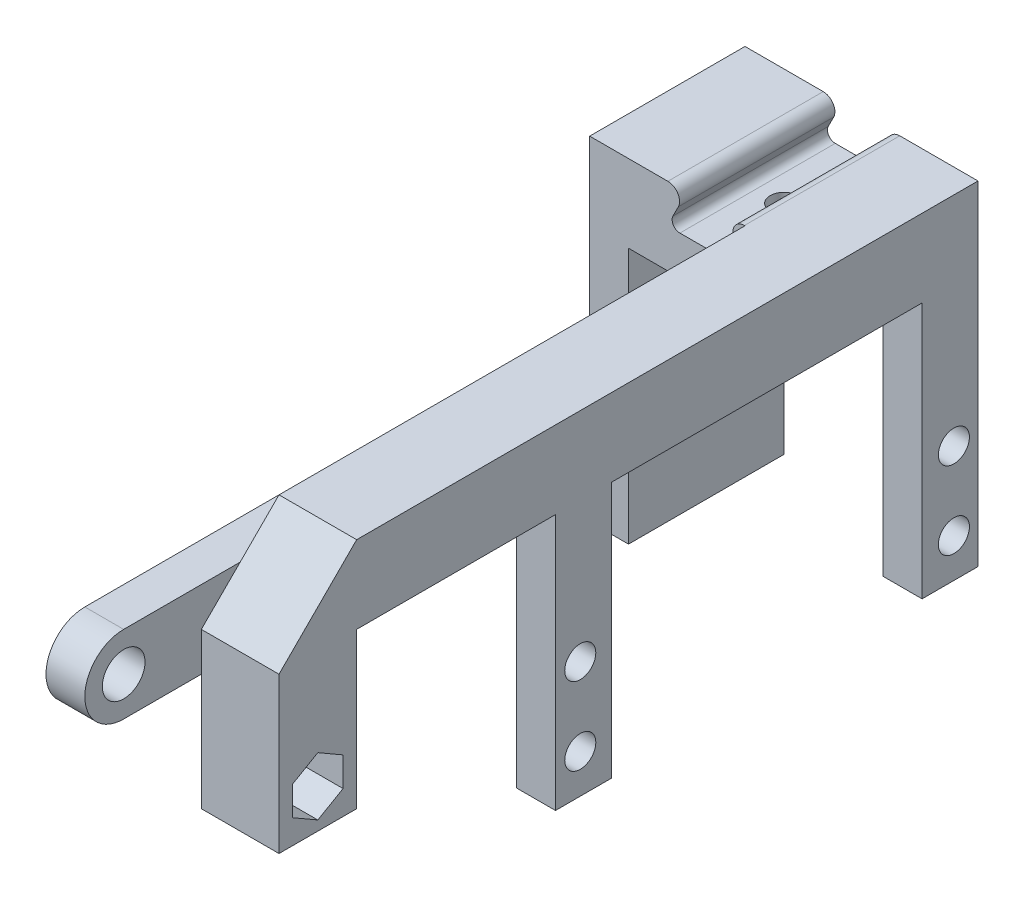
SolidWorks part; units mm, degrees
ref_plane "Plano frontal" through (0, 0, 0) normal (0, 0, 1) x (1, 0, 0)
ref_plane "Plano superior" through (0, 0, 0) normal (0, 1, 0) x (1, 0, 0)
ref_plane "Plano direito" through (0, 0, 0) normal (1, 0, 0) x (0, 0, -1)
sketch "Esboço1" plane through (0, 0, 0) normal (0, 0, 1) x (1, 0, 0)
  line L0 (-15, 45) -> (-15, 2)
  line L1 (-15, 2) -> (-10, 2)
  line L2 (-10, 2) -> (-10, 35)
  line L3 (-10, 35) -> (10, 35)
  line L4 (10, 35) -> (10, -35)
  line L5 (10, -35) -> (-15, -35)
  line L8 (-15, -35) -> (-15, -45)
  line L9 (-15, -45) -> (15, -45)
  line L10 (15, -45) -> (15, 45)
  line L11 (15, 45) -> (-15, 45)
  line L13 (-2.5, 45) -> (-5, 40)
  line L14 (-5, 40) -> (5, 40)
  line L15 (5, 40) -> (2.5, 45)
  point P12 (15, 0)
  point P13 (0, 45)
  point P21 (0, 40)
  dimension "D1" = 30
  dimension "D2" = 5
  dimension "D3" = 10
  dimension "D4" = 5
  dimension "D5" = 20
  dimension "D6" = 10
  dimension "D8" = 90
  dimension "D9" = 33
  dimension "D10" = 10
  dimension "D11" = 5
  dimension "D12" = 5
extrude "Ressalto-extrusão1" add sketch "Esboço1" along normal blind 80 contours L15 L14 L13 L11 L0 L1 L2 L3 L4 L5 L8 L9 L10
sketch "Esboço2" plane through (-15, 0, 0) normal (-1, 0, 0) x (0, 0, 1)
  line L0 (80, 2) -> (0, 2) construction
  line L1 (7.2, 2) -> (47.2, 2)
  line L2 (7.2, 2) -> (7.2, 35)
  line L3 (7.2, 35) -> (47.2, 35)
  line L4 (47.2, 2) -> (47.2, 35)
  line L5 (80, 45) -> (80, 2) construction
  line L6 (54.4, 2) -> (80, 2)
  line L7 (54.4, 2) -> (54.4, 35)
  line L8 (54.4, 35) -> (80, 35)
  line L9 (80, 2) -> (80, 35)
  line L10 (80, 45) -> (0, 45) construction
  dimension "D1" = 40
  dimension "D2" = 10
  dimension "D3" = 7.2
  dimension "D4" = 7.2
  dimension "D5" = 10
extrude "Corte-extrusão1" cut sketch "Esboço2" against normal blind 12
sketch "Esboço4" plane through (-10, 0, 0) normal (1, 0, 0) x (0, 0, -1)
  circle A0 centre (-3.1042, 17.0025) radius 2
  circle A1 centre (-3.1042, 7.0008) radius 2
  circle A2 centre (-51.2105, 17.0025) radius 2
  circle A3 centre (-51.2105, 7.0008) radius 2
extrude "Corte-extrusão3" cut sketch "Esboço4" against normal blind 12
sketch "Esboço6" plane through (-15, 0, 0) normal (-1, 0, 0) x (0, 0, 1)
  line L0 (80, 45) -> (90, 35)
  line L1 (80, 35) -> (90, 35)
  line L2 (80, 35) -> (80, 15)
  line L3 (80, 15) -> (90, 15)
  line L4 (90, 35) -> (90, 15)
  line M16 (80, 35) -> (80, 45)
  dimension "D1" = 10
  dimension "D2" = 20
extrude "Ressalto-extrusão2" add sketch "Esboço6" against normal blind 10 contours L4 L1 L2 L3 | L1 L0 M16
sketch "Esboço7" plane through (-15, 0, 0) normal (-1, 0, 0) x (0, 0, 1)
  line L0 (90, 35) -> (90, 15) construction
  line L1 (80, 15) -> (90, 15) construction
  circle A0 centre (85, 20) radius 1.75
  dimension "D1" = 3.5
  dimension "D2" = 5
  dimension "D3" = 5
extrude "Corte-extrusão4" cut sketch "Esboço7" against normal blind 15
sketch "Esboço8" plane through (-15, 0, 0) normal (-1, 0, 0) x (0, 0, 1)
  line L1 (85, 23.7528) -> (81.75, 21.8764)
  line L2 (81.75, 21.8764) -> (81.75, 18.1236)
  line L3 (81.75, 18.1236) -> (85, 16.2472)
  line L4 (85, 16.2472) -> (88.25, 18.1236)
  line L5 (88.25, 18.1236) -> (88.25, 21.8764)
  line L6 (88.25, 21.8764) -> (85, 23.7528)
  circle A0 centre (85, 20) radius 3.25 construction
  dimension "D1" = 6.5
extrude "Corte-extrusão5" cut sketch "Esboço8" against normal blind 5
sketch "Esboço10" plane through (15, 0, 0) normal (1, 0, 0) x (0, 0, -1)
  line L0 (-85, 25) -> (-80, 25)
  line L1 (-80, 35) -> (-80, 15) construction
  line L2 (-80, 25) -> (-80, 15)
  line L3 (-80, 15) -> (-85, 15)
  circle A0 centre (-85, 20) radius 2.75
  circle A1 centre (-85, 20) radius 5
  line M4 (-80, 45) -> (-80, -45)
  dimension "D1" = 5.5
extrude "Ressalto-extrusão3" add sketch "Esboço10" against normal blind 5 contours A1 L0 M4 | A1 A0 | A1 L3 L2
sketch "Esboço11" plane through (0, 0, 80) normal (0, 0, 1) x (1, 0, 0)
  line L1 (15, -45) -> (10, -45)
  line L2 (15, -45) -> (15, 15)
  line L3 (15, 15) -> (10, 15)
  line L4 (10, -45) -> (10, 15)
  line L5 (-5, 45) -> (15, 45)
  line L6 (-5, 45) -> (-5, 25)
  line L7 (-5, 25) -> (15, 25)
  line L8 (15, 45) -> (15, 25)
  line L9 (-15, -35) -> (10, -35)
  line L10 (-15, -35) -> (-15, -45)
  line L11 (-15, -45) -> (10, -45)
  line L12 (10, -35) -> (10, -45)
  line M1 (15, -45) -> (15, 15)
  line M2 (15, 15) -> (10, 15)
  line M3 (10, 15) -> (10, -35)
  line M4 (10, -35) -> (-15, -35)
  line M5 (-15, -35) -> (-15, -45)
  line M6 (-15, -45) -> (15, -45)
extrude "Corte-extrusão7" cut sketch "Esboço11" against normal blind 60 contours L8 L5 L6 L7 | L4 M6 M1 M2 M3 | L4 M6 M4 M5
sketch "Esboço13" plane through (0, 0, 20) normal (0, 0, 1) x (1, 0, 0)
  line L0 (15, -45) -> (15, 15) construction
  line L1 (-15, -45) -> (15, -45)
  line L2 (-15, -45) -> (-15, 2)
  line L3 (-15, 2) -> (15, 2)
  line L4 (15, -45) -> (15, 2)
  line L5 (-10, 2) -> (-15, 2) construction
extrude "Corte-extrusão9" cut sketch "Esboço13" against normal blind 168
fillet "Filete1" radius 1.5 2 edges at (2.5, 45, 10) (-2.5, 45, 10)
sketch "Esboço14" plane through (0, 40, 0) normal (0, 1, 0) x (1, 0, 0)
  line L0 (-5, -20) -> (5, -20) construction
  line L1 (15, -20) -> (15, 0) construction
  circle A0 centre (0, -10) radius 1.75
  dimension "D1" = 3.5
  dimension "D2" = 10
  dimension "D3" = 15
extrude "Corte-extrusão10" cut sketch "Esboço14" against normal blind 14.5
sketch "Esboço15" plane through (0, 35, 0) normal (0, -1, 0) x (1, 0, 0)
  line L1 (0, 13.7528) -> (-3.25, 11.8764)
  line L2 (-3.25, 11.8764) -> (-3.25, 8.1236)
  line L3 (-3.25, 8.1236) -> (0, 6.2472)
  line L4 (0, 6.2472) -> (3.25, 8.1236)
  line L5 (3.25, 8.1236) -> (3.25, 11.8764)
  line L6 (3.25, 11.8764) -> (0, 13.7528)
  circle A0 centre (0, 10) radius 3.25 construction
  dimension "D1" = 6.5
extrude "Corte-extrusão11" cut sketch "Esboço15" against normal blind 2.5
fillet "Filete2" radius 1 2 edges at (5, 40, 10) (-5, 40, 10)
mirror "Espelhar1" about plane through (-15, 0, 80) normal (1, 0, 0) of bodies 114
sketch "Esboço16" plane through (0, 0, 90) normal (0, 0, 1) x (1, 0, 0)
  line L0 (-5, 45) -> (-25, 45) construction
  line L1 (-15, 45) -> (15, 45)
  line L2 (-15, 45) -> (-15, 2)
  line L3 (-15, 2) -> (15, 2)
  line L4 (15, 45) -> (15, 2)
extrude "Corte-extrusão12" cut sketch "Esboço16" against normal blind 120
